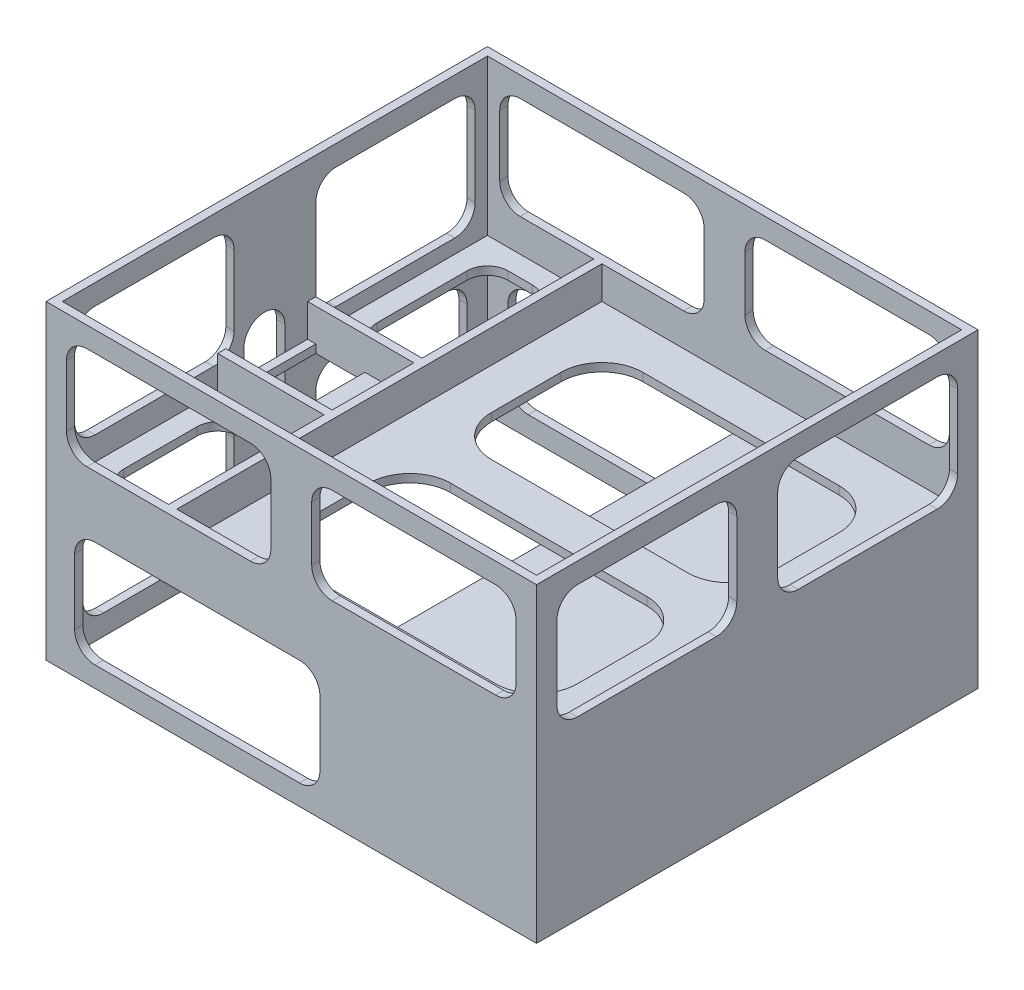
SolidWorks part; units mm, degrees
ref_plane "Front Plane" through (0, 0, 0) normal (0, 0, 1) x (1, 0, 0)
ref_plane "Top Plane" through (0, 0, 0) normal (0, 1, 0) x (1, 0, 0)
ref_plane "Right Plane" through (0, 0, 0) normal (1, 0, 0) x (0, 0, -1)
sketch "Sketch1" plane through (0, 0, 0) normal (0, 1, 0) x (1, 0, 0)
  line L1 (-113.8745, -60.9464) -> (-53.8745, -60.9464)
  line L2 (-113.8745, -60.9464) -> (-113.8745, -6.9464)
  line L3 (-113.8745, -6.9464) -> (-53.8745, -6.9464)
  line L4 (-53.8745, -60.9464) -> (-53.8745, -6.9464)
  dimension "D1" = 60
  dimension "D2" = 54
extrude "Boss-Extrude1" add sketch "Sketch1" along normal blind 38
sketch "Sketch2" plane through (0, 38, 0) normal (0, 1, 0) x (1, 0, 0)
  line L0 (-53.8745, -60.9464) -> (-53.8745, -6.9464) construction
  line L1 (-54.8745, -7.9464) -> (-98.8745, -7.9464)
  line L2 (-54.8745, -7.9464) -> (-54.8745, -59.9464)
  line L3 (-54.8745, -59.9464) -> (-98.8745, -59.9464)
  line L4 (-98.8745, -7.9464) -> (-98.8745, -59.9464)
  line L5 (-53.8745, -6.9464) -> (-113.8745, -6.9464) construction
  line L6 (-113.8745, -60.9464) -> (-53.8745, -60.9464) construction
  dimension "D1" = 1
  dimension "D2" = 1
  dimension "D3" = 1
  dimension "D4" = 44
extrude "Cut-Extrude1" cut sketch "Sketch2" against normal blind 19
sketch "Sketch3" plane through (0, 0, 0) normal (0, -1, 0) x (-1, 0, 0)
  line L0 (113.8745, -60.9464) -> (53.8745, -60.9464) construction
  line L1 (112.8745, -59.9464) -> (77.8745, -59.9464)
  line L2 (112.8745, -59.9464) -> (112.8745, -7.9464)
  line L3 (112.8745, -7.9464) -> (77.8745, -7.9464)
  line L4 (77.8745, -59.9464) -> (77.8745, -7.9464)
  line L5 (113.8745, -6.9464) -> (113.8745, -60.9464) construction
  line L6 (53.8745, -6.9464) -> (113.8745, -6.9464) construction
  dimension "D1" = 1
  dimension "D2" = 35
  dimension "D3" = 1
  dimension "D4" = 1
extrude "Cut-Extrude2" cut sketch "Sketch3" against normal blind 18
sketch "Sketch4" plane through (0, 18, 0) normal (0, -1, 0) x (-1, 0, 0)
  line L0 (77.8745, -59.9464) -> (112.8745, -59.9464) construction
  line L1 (111.8745, -39.9464) -> (105.8745, -39.9464)
  line L2 (111.8745, -39.9464) -> (111.8745, -29.9464)
  line L3 (111.8745, -29.9464) -> (105.8745, -29.9464)
  line L4 (105.8745, -39.9464) -> (105.8745, -29.9464)
  line L5 (112.8745, -7.9464) -> (77.8745, -7.9464) construction
  line L6 (112.8745, -59.9464) -> (112.8745, -7.9464) construction
  dimension "D1" = 20
  dimension "D2" = 22
  dimension "D3" = 1
  dimension "D4" = 6
extrude "Cut-Extrude3" cut sketch "Sketch4" against normal blind 38
sketch "Sketch5" plane through (0, 38, 0) normal (0, 1, 0) x (1, 0, 0)
  line L0 (-53.8745, -6.9464) -> (-113.8745, -6.9464) construction
  line L1 (-98.8745, -59.9464) -> (-112.8745, -59.9464)
  line L2 (-98.8745, -59.9464) -> (-98.8745, -7.9464)
  line L3 (-98.8745, -7.9464) -> (-112.8745, -7.9464)
  line L4 (-112.8745, -59.9464) -> (-112.8745, -7.9464)
  line L5 (-113.8745, -6.9464) -> (-113.8745, -60.9464) construction
  dimension "D1" = 1
  dimension "D2" = 1
extrude "Cut-Extrude5" cut sketch "Sketch5" against normal blind 15
sketch "Sketch6" plane through (0, 23, 0) normal (0, 1, 0) x (1, 0, 0)
  line L0 (-112.8745, -59.9464) -> (-98.8745, -59.9464) construction
  line L1 (-112.8745, -7.9464) -> (-99.8745, -7.9464)
  line L2 (-112.8745, -7.9464) -> (-112.8745, -59.9464)
  line L3 (-112.8745, -59.9464) -> (-99.8745, -59.9464)
  line L4 (-99.8745, -7.9464) -> (-99.8745, -59.9464)
  line L5 (-98.8745, -59.9464) -> (-98.8745, -7.9464) construction
  dimension "D1" = 1
extrude "Cut-Extrude6" cut sketch "Sketch6" against normal blind 4
sketch "Sketch8" plane through (0, 0, 0) normal (0, -1, 0) x (-1, 0, 0)
  line L0 (53.8745, -60.9464) -> (53.8745, -6.9464) construction
  line L1 (73.3745, -11.4464) -> (58.3745, -11.4464)
  line L2 (73.3745, -11.4464) -> (73.3745, -24.4464)
  line L3 (73.3745, -24.4464) -> (58.3745, -24.4464)
  line L4 (58.3745, -11.4464) -> (58.3745, -24.4464)
  line L6 (53.8745, -6.9464) -> (113.8745, -6.9464) construction
  dimension "D1" = 15
  dimension "D2" = 13
  dimension "D3" = 4.5
  dimension "D4" = 4.5
extrude "Cut-Extrude7" cut sketch "Sketch8" against normal blind 6
sketch "Sketch10" plane through (-73.3745, 0, 0) normal (1, 0, 0) x (0, 0, -1)
  line L0 (-11.4464, 6) -> (-11.4464, 0) construction
  line L1 (-24.4464, 6) -> (-11.4464, 6)
  line L2 (-24.4464, 6) -> (-24.4464, 1)
  line L3 (-24.4464, 1) -> (-11.4464, 1)
  line L4 (-11.4464, 6) -> (-11.4464, 1)
  line L5 (-24.4464, 0) -> (-11.4464, 0) construction
  dimension "D1" = 1
extrude "Cut-Extrude8" cut sketch "Sketch10" against normal blind 6
sketch "Sketch11" plane through (0, 0, 0) normal (0, -1, 0) x (1, 0, 0)
  line L0 (-113.8745, 60.9464) -> (-53.8745, 60.9464) construction
  line L1 (-67.8745, 50.9464) -> (-63.8745, 50.9464)
  line L2 (-67.8745, 50.9464) -> (-67.8745, 45.9464)
  line L3 (-67.8745, 45.9464) -> (-63.8745, 45.9464)
  line L4 (-63.8745, 50.9464) -> (-63.8745, 45.9464)
  line L5 (-53.8745, 60.9464) -> (-53.8745, 6.9464) construction
  dimension "D1" = 4
  dimension "D2" = 5
  dimension "D3" = 10
  dimension "D4" = 10
extrude "Cut-Extrude9" cut sketch "Sketch11" against normal blind 3
sketch "Sketch12" plane through (-67.8745, 0, 0) normal (1, 0, 0) x (0, 0, -1)
  line L0 (-50.9464, 3) -> (-50.9464, 0) construction
  line L1 (-45.9464, 3) -> (-50.9464, 3)
  line L2 (-45.9464, 3) -> (-45.9464, 1)
  line L3 (-45.9464, 1) -> (-50.9464, 1)
  line L4 (-50.9464, 3) -> (-50.9464, 1)
  line L5 (-50.9464, 0) -> (-45.9464, 0) construction
  dimension "D1" = 1
extrude "Cut-Extrude10" cut sketch "Sketch12" against normal blind 13
sketch "Sketch13" plane through (-113.8745, 0, 0) normal (-1, 0, 0) x (0, 0, 1)
  line L0 (35.233, 15) -> (35.233, 22) construction
  line L1 (32.733, 15) -> (32.733, 22)
  line L2 (37.733, 15) -> (37.733, 22)
  line L3 (59.9464, 18) -> (7.9464, 18) construction
  line L4 (39.9464, 19) -> (29.9464, 19) construction
  arc A0 (32.733, 15) -> (37.733, 15) centre (35.233, 15) ccw
  arc A1 (37.733, 22) -> (32.733, 22) centre (35.233, 22) ccw
  point P2 (35.233, 18.5)
  dimension "D1" = 3
  dimension "D2" = 3
  dimension "D3" = 2.5
extrude "Cut-Extrude11" cut sketch "Sketch13" against normal blind 1
sketch "Sketch14" plane through (0, 19, 0) normal (0, 1, 0) x (1, 0, 0)
  line L0 (-99.8745, -59.9464) -> (-99.8745, -7.9464) construction
  line L1 (-112.8745, -40.9464) -> (-99.8745, -40.9464)
  line L2 (-112.8745, -40.9464) -> (-112.8745, -39.9464)
  line L3 (-112.8745, -39.9464) -> (-99.8745, -39.9464)
  line L4 (-99.8745, -40.9464) -> (-99.8745, -39.9464)
  line L5 (-112.8745, -37.733) -> (-112.8745, -59.9464) construction
  line L6 (-105.8745, -39.9464) -> (-111.8745, -39.9464) construction
  dimension "D1" = 0
  dimension "D2" = 1
  dimension "D3" = 0
extrude "Boss-Extrude2" add sketch "Sketch14" along normal blind 4
sketch "Sketch15" plane through (0, 19, 0) normal (0, 1, 0) x (1, 0, 0)
  line L0 (-112.8745, -7.9464) -> (-112.8745, -32.733) construction
  line L1 (-112.8745, -29.9464) -> (-99.8745, -29.9464)
  line L2 (-112.8745, -29.9464) -> (-112.8745, -28.9464)
  line L3 (-112.8745, -28.9464) -> (-99.8745, -28.9464)
  line L4 (-99.8745, -29.9464) -> (-99.8745, -28.9464)
  line L5 (-99.8745, -39.9464) -> (-99.8745, -7.9464) construction
  line L6 (-111.8745, -29.9464) -> (-105.8745, -29.9464) construction
  dimension "D1" = 0
  dimension "D2" = 1
extrude "Boss-Extrude3" add sketch "Sketch15" along normal blind 4
sketch "Sketch16" plane through (0, 19, 0) normal (0, 1, 0) x (1, 0, 0)
  line L0 (-98.8745, -59.9464) -> (-54.8745, -59.9464) construction
  line L1 (-64.8745, -54.9464) -> (-88.8745, -54.9464)
  line L2 (-59.8745, -49.9464) -> (-59.8745, -41.4464)
  line L3 (-64.8745, -36.4464) -> (-88.8745, -36.4464)
  line L4 (-93.8745, -49.9464) -> (-93.8745, -41.4464)
  line L5 (-88.8745, -31.4464) -> (-64.8745, -31.4464)
  line L6 (-93.8745, -26.4464) -> (-93.8745, -17.9464)
  line L7 (-88.8745, -12.9464) -> (-64.8745, -12.9464)
  line L8 (-59.8745, -26.4464) -> (-59.8745, -17.9464)
  line L9 (-54.8745, -59.9464) -> (-54.8745, -7.9464) construction
  line L10 (-98.8745, -7.9464) -> (-98.8745, -59.9464) construction
  line L11 (-54.8745, -7.9464) -> (-98.8745, -7.9464) construction
  arc A0 (-64.8745, -31.4464) -> (-59.8745, -26.4464) centre (-64.8745, -26.4464) ccw
  arc A1 (-64.8745, -12.9464) -> (-59.8745, -17.9464) centre (-64.8745, -17.9464) cw
  arc A2 (-93.8745, -17.9464) -> (-88.8745, -12.9464) centre (-88.8745, -17.9464) cw
  arc A3 (-88.8745, -31.4464) -> (-93.8745, -26.4464) centre (-88.8745, -26.4464) cw
  arc A4 (-88.8745, -54.9464) -> (-93.8745, -49.9464) centre (-88.8745, -49.9464) cw
  arc A5 (-88.8745, -36.4464) -> (-93.8745, -41.4464) centre (-88.8745, -41.4464) ccw
  arc A6 (-59.8745, -41.4464) -> (-64.8745, -36.4464) centre (-64.8745, -41.4464) ccw
  arc A7 (-64.8745, -54.9464) -> (-59.8745, -49.9464) centre (-64.8745, -49.9464) ccw
  point P22 (-93.8745, -12.9464)
  point P25 (-93.8745, -31.4464)
  dimension "D9" = 5
  dimension "D1" = 5
  dimension "D2" = 5
  dimension "D3" = 5
  dimension "D4" = 5
  dimension "D5" = 5
  dimension "D6" = 5
  dimension "D7" = 5
  dimension "D8" = 18.5
extrude "Cut-Extrude12" cut sketch "Sketch16" against normal blind 1
sketch "Sketch17" plane through (0, 19, 0) normal (0, 1, 0) x (1, 0, 0)
  line L0 (-112.8745, -40.9464) -> (-112.8745, -59.9464) construction
  line L1 (-104.8745, -57.4464) -> (-107.8745, -57.4464)
  line L2 (-102.3745, -54.9464) -> (-102.3745, -45.9464)
  line L3 (-104.8745, -43.4464) -> (-107.8745, -43.4464)
  line L4 (-110.3745, -54.9464) -> (-110.3745, -45.9464)
  line L5 (-104.8745, -26.4464) -> (-107.8745, -26.4464)
  line L6 (-102.3745, -23.9464) -> (-102.3745, -12.9464)
  line L7 (-104.8745, -10.4464) -> (-107.8745, -10.4464)
  line L8 (-110.3745, -23.9464) -> (-110.3745, -12.9464)
  line L9 (-99.8745, -59.9464) -> (-99.8745, -40.9464) construction
  line L10 (-112.8745, -40.9464) -> (-99.8745, -40.9464) construction
  line L11 (-112.8745, -59.9464) -> (-99.8745, -59.9464) construction
  line L12 (-99.8745, -28.9464) -> (-112.8745, -28.9464) construction
  line L13 (-112.8745, -7.9464) -> (-112.8745, -28.9464) construction
  line L14 (-99.8745, -28.9464) -> (-99.8745, -7.9464) construction
  line L15 (-99.8745, -7.9464) -> (-112.8745, -7.9464) construction
  arc A0 (-102.3745, -12.9464) -> (-104.8745, -10.4464) centre (-104.8745, -12.9464) ccw
  arc A1 (-107.8745, -10.4464) -> (-110.3745, -12.9464) centre (-107.8745, -12.9464) ccw
  arc A2 (-107.8745, -26.4464) -> (-110.3745, -23.9464) centre (-107.8745, -23.9464) cw
  arc A3 (-104.8745, -26.4464) -> (-102.3745, -23.9464) centre (-104.8745, -23.9464) ccw
  arc A4 (-102.3745, -45.9464) -> (-104.8745, -43.4464) centre (-104.8745, -45.9464) ccw
  arc A5 (-107.8745, -43.4464) -> (-110.3745, -45.9464) centre (-107.8745, -45.9464) ccw
  arc A6 (-107.8745, -57.4464) -> (-110.3745, -54.9464) centre (-107.8745, -54.9464) cw
  arc A7 (-104.8745, -57.4464) -> (-102.3745, -54.9464) centre (-104.8745, -54.9464) ccw
  dimension "D9" = 2.5
  dimension "D1" = 2.5
  dimension "D2" = 2.5
  dimension "D3" = 2.5
  dimension "D4" = 2.5
  dimension "D5" = 2.5
  dimension "D6" = 2.5
  dimension "D7" = 2.5
  dimension "D8" = 2.5
extrude "Cut-Extrude13" cut sketch "Sketch17" against normal blind 1
sketch "Sketch18" plane through (-53.8745, 0, 0) normal (1, 0, 0) x (0, 0, -1)
  line L0 (-60.9464, 38) -> (-6.9464, 38) construction
  line L1 (-55.9464, 35.5) -> (-38.9464, 35.5)
  line L2 (-58.4464, 33) -> (-58.4464, 24)
  line L3 (-55.9464, 21.5) -> (-38.9464, 21.5)
  line L4 (-36.4464, 33) -> (-36.4464, 24)
  line L5 (-28.9464, 35.5) -> (-11.9464, 35.5)
  line L6 (-31.4464, 33) -> (-31.4464, 24)
  line L7 (-28.9464, 21.5) -> (-11.9464, 21.5)
  line L8 (-9.4464, 33) -> (-9.4464, 24)
  line L9 (-60.9464, 38) -> (-60.9464, 0) construction
  line L10 (-6.9464, 38) -> (-6.9464, 0) construction
  line L11 (-59.9464, 19) -> (-7.9464, 19) construction
  arc A0 (-31.4464, 24) -> (-28.9464, 21.5) centre (-28.9464, 24) ccw
  arc A1 (-11.9464, 21.5) -> (-9.4464, 24) centre (-11.9464, 24) ccw
  arc A2 (-11.9464, 35.5) -> (-9.4464, 33) centre (-11.9464, 33) cw
  arc A3 (-28.9464, 35.5) -> (-31.4464, 33) centre (-28.9464, 33) ccw
  arc A4 (-58.4464, 24) -> (-55.9464, 21.5) centre (-55.9464, 24) ccw
  arc A5 (-38.9464, 21.5) -> (-36.4464, 24) centre (-38.9464, 24) ccw
  arc A6 (-38.9464, 35.5) -> (-36.4464, 33) centre (-38.9464, 33) cw
  arc A7 (-55.9464, 35.5) -> (-58.4464, 33) centre (-55.9464, 33) ccw
  point P26 (-58.4464, 21.5)
  point P29 (-36.4464, 21.5)
  dimension "D9" = 2.5
  dimension "D1" = 2.5
  dimension "D2" = 2.5
  dimension "D3" = 2.5
  dimension "D4" = 2.5
  dimension "D5" = 5
  dimension "D6" = 22
  dimension "D7" = 2.5
  dimension "D8" = 2.5
extrude "Cut-Extrude14" cut sketch "Sketch18" against normal blind 1
sketch "Sketch19" plane through (0, 0, 6.9464) normal (0, 0, -1) x (-1, 0, 0)
  line L0 (53.8745, 38) -> (113.8745, 38) construction
  line L1 (58.8745, 35.5) -> (78.8745, 35.5)
  line L2 (56.3745, 33) -> (56.3745, 26.3041)
  line L3 (58.8745, 23.8041) -> (78.8745, 23.8041)
  line L4 (81.3745, 33) -> (81.3745, 26.3041)
  line L5 (88.8745, 35.5) -> (108.8745, 35.5)
  line L6 (86.3745, 33) -> (86.3745, 25.5)
  line L7 (88.8745, 23) -> (108.8745, 23)
  line L8 (111.3745, 33) -> (111.3745, 25.5)
  line L9 (113.8745, 38) -> (113.8745, 0) construction
  line L10 (53.8745, 38) -> (53.8745, 0) construction
  arc A0 (108.8745, 23) -> (111.3745, 25.5) centre (108.8745, 25.5) ccw
  arc A1 (108.8745, 35.5) -> (111.3745, 33) centre (108.8745, 33) cw
  arc A2 (88.8745, 35.5) -> (86.3745, 33) centre (88.8745, 33) ccw
  arc A3 (86.3745, 25.5) -> (88.8745, 23) centre (88.8745, 25.5) ccw
  arc A4 (78.8745, 23.8041) -> (81.3745, 26.3041) centre (78.8745, 26.3041) ccw
  arc A5 (78.8745, 35.5) -> (81.3745, 33) centre (78.8745, 33) cw
  arc A6 (56.3745, 26.3041) -> (58.8745, 23.8041) centre (58.8745, 26.3041) ccw
  arc A7 (58.8745, 35.5) -> (56.3745, 33) centre (58.8745, 33) ccw
  point P17 (111.3745, 23)
  point P24 (86.3745, 23)
  dimension "D8" = 2.5
  dimension "D1" = 2.5
  dimension "D2" = 2.5
  dimension "D3" = 2.5
  dimension "D4" = 2.5
  dimension "D5" = 5
  dimension "D6" = 25
  dimension "D7" = 0
extrude "Cut-Extrude15" cut sketch "Sketch19" against normal blind 60
sketch "Sketch20" plane through (-113.8745, 0, 0) normal (-1, 0, 0) x (0, 0, 1)
  line L0 (59.9464, 38) -> (7.9464, 38) construction
  line L1 (11.9464, 35.5) -> (26.4464, 35.5)
  line L2 (9.4464, 33) -> (9.4464, 23.222)
  line L3 (11.9464, 20.722) -> (26.4464, 20.722)
  line L4 (28.9464, 33) -> (28.9464, 23.222)
  line L5 (41.4464, 35.5) -> (55.9464, 35.5)
  line L6 (38.9464, 33) -> (38.9464, 24.3756)
  line L7 (41.4464, 21.8756) -> (55.9464, 21.8756)
  line L8 (58.4464, 33) -> (58.4464, 24.3756)
  line L9 (6.9464, 38) -> (6.9464, 0) construction
  line L10 (60.9464, 38) -> (60.9464, 0) construction
  line L11 (6.9464, 38) -> (60.9464, 38) construction
  arc A0 (38.9464, 24.3756) -> (41.4464, 21.8756) centre (41.4464, 24.3756) ccw
  arc A1 (55.9464, 21.8756) -> (58.4464, 24.3756) centre (55.9464, 24.3756) ccw
  arc A2 (55.9464, 35.5) -> (58.4464, 33) centre (55.9464, 33) cw
  arc A3 (41.4464, 35.5) -> (38.9464, 33) centre (41.4464, 33) ccw
  arc A4 (9.4464, 23.222) -> (11.9464, 20.722) centre (11.9464, 23.222) ccw
  arc A5 (26.4464, 20.722) -> (28.9464, 23.222) centre (26.4464, 23.222) ccw
  arc A6 (26.4464, 35.5) -> (28.9464, 33) centre (26.4464, 33) cw
  arc A7 (11.9464, 35.5) -> (9.4464, 33) centre (11.9464, 33) ccw
  point P18 (38.9464, 21.8756)
  point P21 (58.4464, 21.8756)
  dimension "D7" = 2.5
  dimension "D1" = 2.5
  dimension "D2" = 2.5
  dimension "D3" = 10
  dimension "D4" = 2.5
  dimension "D5" = 2.5
  dimension "D6" = 19.5
extrude "Cut-Extrude16" cut sketch "Sketch20" against normal blind 1
sketch "Sketch21" plane through (0, 0, 59.9464) normal (0, 0, -1) x (-1, 0, 0)
  line L0 (77.8745, 0) -> (112.8745, 0) construction
  line L1 (107.8745, 2.5) -> (82.8745, 2.5)
  line L2 (110.3745, 5) -> (110.3745, 13)
  line L3 (107.8745, 15.5) -> (82.8745, 15.5)
  line L4 (80.3745, 5) -> (80.3745, 13)
  line L5 (77.8745, 18) -> (77.8745, 0) construction
  line L6 (112.8745, 18) -> (112.8745, 0) construction
  line L7 (77.8745, 18) -> (112.8745, 18) construction
  arc A0 (110.3745, 13) -> (107.8745, 15.5) centre (107.8745, 13) ccw
  arc A1 (82.8745, 15.5) -> (80.3745, 13) centre (82.8745, 13) ccw
  arc A2 (82.8745, 2.5) -> (80.3745, 5) centre (82.8745, 5) cw
  arc A3 (107.8745, 2.5) -> (110.3745, 5) centre (107.8745, 5) ccw
  dimension "D5" = 2.5
  dimension "D1" = 2.5
  dimension "D2" = 2.5
  dimension "D3" = 2.5
  dimension "D4" = 2.5
extrude "Cut-Extrude17" cut sketch "Sketch21" along normal blind 100 and the other way blind 10
sketch "Sketch22" plane through (-112.8745, 0, 0) normal (1, 0, 0) x (0, 0, -1)
  line L0 (-59.9464, 0) -> (-7.9464, 0) construction
  line L1 (-12.9464, 2.5) -> (-26.4464, 2.5)
  line L2 (-10.4464, 5) -> (-10.4464, 13)
  line L3 (-12.9464, 15.5) -> (-26.4464, 15.5)
  line L4 (-28.9464, 5) -> (-28.9464, 13)
  line L5 (-41.4464, 2.5) -> (-54.9464, 2.5)
  line L6 (-38.9464, 5) -> (-38.9464, 13)
  line L7 (-41.4464, 15.5) -> (-54.9464, 15.5)
  line L8 (-57.4464, 5) -> (-57.4464, 13)
  line L9 (-7.9464, 18) -> (-7.9464, 0) construction
  line L10 (-32.733, 18) -> (-7.9464, 18) construction
  line L11 (-59.9464, 18) -> (-37.733, 18) construction
  line L12 (-59.9464, 18) -> (-59.9464, 0) construction
  arc A0 (-38.9464, 13) -> (-41.4464, 15.5) centre (-41.4464, 13) ccw
  arc A1 (-54.9464, 15.5) -> (-57.4464, 13) centre (-54.9464, 13) ccw
  arc A2 (-54.9464, 2.5) -> (-57.4464, 5) centre (-54.9464, 5) cw
  arc A3 (-41.4464, 2.5) -> (-38.9464, 5) centre (-41.4464, 5) ccw
  arc A4 (-26.4464, 2.5) -> (-28.9464, 5) centre (-26.4464, 5) cw
  arc A5 (-26.4464, 15.5) -> (-28.9464, 13) centre (-26.4464, 13) ccw
  arc A6 (-10.4464, 13) -> (-12.9464, 15.5) centre (-12.9464, 13) ccw
  arc A7 (-12.9464, 2.5) -> (-10.4464, 5) centre (-12.9464, 5) ccw
  point P30 (-28.9464, 15.5)
  point P33 (-10.4464, 15.5)
  dimension "D9" = 2.5
  dimension "D1" = 2.5
  dimension "D2" = 10
  dimension "D3" = 2.5
  dimension "D4" = 2.5
  dimension "D5" = 2.5
  dimension "D6" = 2.5
  dimension "D7" = 2.5
  dimension "D8" = 18.5
extrude "Cut-Extrude18" cut sketch "Sketch22" against normal blind 10
